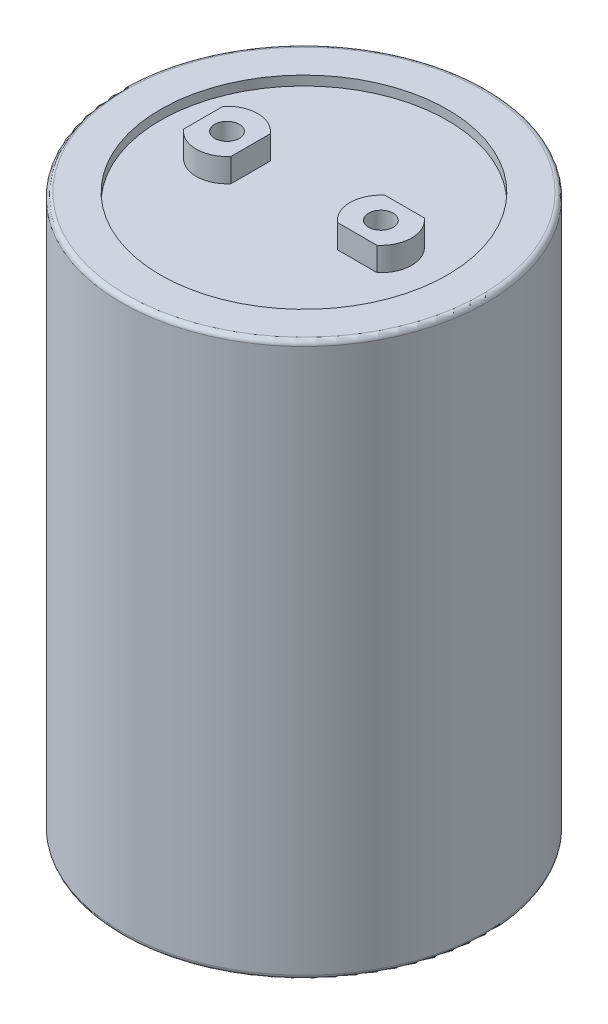
SolidWorks part; units mm, degrees
ref_plane "Front Plane" through (0, 0, 0) normal (0, 0, 1) x (1, 0, 0)
ref_plane "Top Plane" through (0, 0, 0) normal (0, 1, 0) x (1, 0, 0)
ref_plane "Right Plane" through (0, 0, 0) normal (1, 0, 0) x (0, 0, -1)
sketch "Sketch1" plane through (0, 0, 0) normal (0, 1, 0) x (1, 0, 0)
  circle A0 centre (0, 0) radius 38.5
  dimension "D1" = 77
extrude "Boss-Extrude1" add sketch "Sketch1" along normal blind 115
sketch "Sketch2" plane through (0, 115, 0) normal (0, 1, 0) x (1, 0, 0)
  line L0 (-38.5, 0) -> (38.5, 0) construction
  line L1 (0, 0) -> (0, 38.5) construction
  line L2 (-16.25, 0) -> (-16.25, 6.5) construction
  line L3 (-11.25, 4.1533) -> (-11.25, -4.1533) construction
  line L4 (-21.25, -4.1533) -> (-21.25, 4.1533) construction
  line L5 (12.0967, 5) -> (20.4033, 5) construction
  line L6 (20.4033, -5) -> (12.0967, -5) construction
  line L7 (-21.25, 4.1533) -> (-21.25, -4.1533)
  line L8 (-11.25, -4.1533) -> (-11.25, 4.1533)
  line L9 (12.0967, 5) -> (20.4033, 5)
  line L10 (20.4033, -5) -> (12.0967, -5)
  circle A0 centre (0, 0) radius 38.5 construction
  circle A1 centre (16.25, 0) radius 6.5 construction
  circle A2 centre (-16.25, 0) radius 6.5 construction
  arc A3 (-11.25, 4.1533) -> (-21.25, 4.1533) centre (-16.25, 0) ccw
  arc A4 (-11.25, -4.1533) -> (-21.25, -4.1533) centre (-16.25, 0) cw
  arc A5 (12.0967, 5) -> (12.0967, -5) centre (16.25, 0) ccw
  arc A6 (20.4033, 5) -> (20.4033, -5) centre (16.25, 0) cw
  circle A7 centre (-16.25, 0) radius 2.6
  circle A8 centre (16.25, 0) radius 2.6
  dimension "D1" = 13
  dimension "D2" = 13
  dimension "D6" = 5.2
  dimension "D3" = 32.5
  dimension "D4" = 10
  dimension "D5" = 10
extrude "Boss-Extrude2" add sketch "Sketch2" along normal blind 5
sketch "Sketch3" plane through (0, 115, 0) normal (0, 1, 0) x (1, 0, 0)
  circle A0 centre (0, 0) radius 38.5
  circle A1 centre (0, 0) radius 30.3
  circle A2 centre (0, 0) radius 38.5 construction
  dimension "D1" = 8.2
extrude "Boss-Extrude3" add sketch "Sketch3" along normal blind 2
fillet "Fillet1" radius 1 2 edges at (0, 0, 38.5) (0, 117, 38.5)
